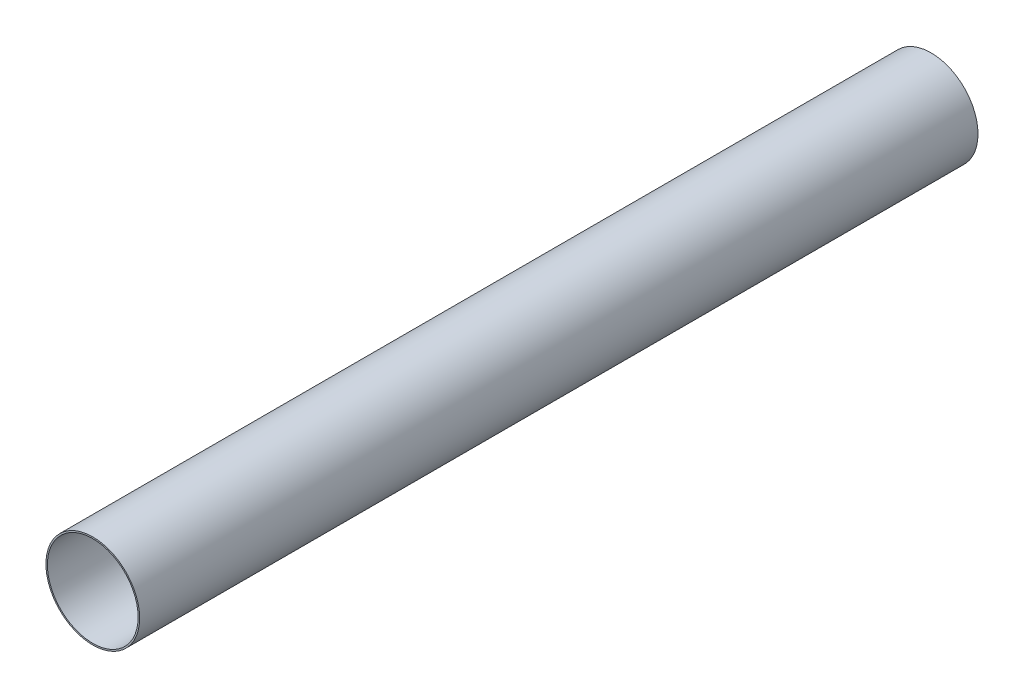
SolidWorks part; units mm, degrees
ref_plane "Front Plane" through (0, 0, 0) normal (0, 0, 1) x (1, 0, 0)
ref_plane "Top Plane" through (0, 0, 0) normal (0, 1, 0) x (1, 0, 0)
ref_plane "Right Plane" through (0, 0, 0) normal (1, 0, 0) x (0, 0, -1)
sketch "Sketch1" plane through (0, 0, 0) normal (0, 0, 1) x (1, 0, 0)
  circle A0 centre (0, 0) radius 38
  circle A1 centre (0, 0) radius 36.8
  dimension "D1" = 76
  dimension "D2" = 1.2
extrude "Boss-Extrude1" add sketch "Sketch1" along normal blind 680
